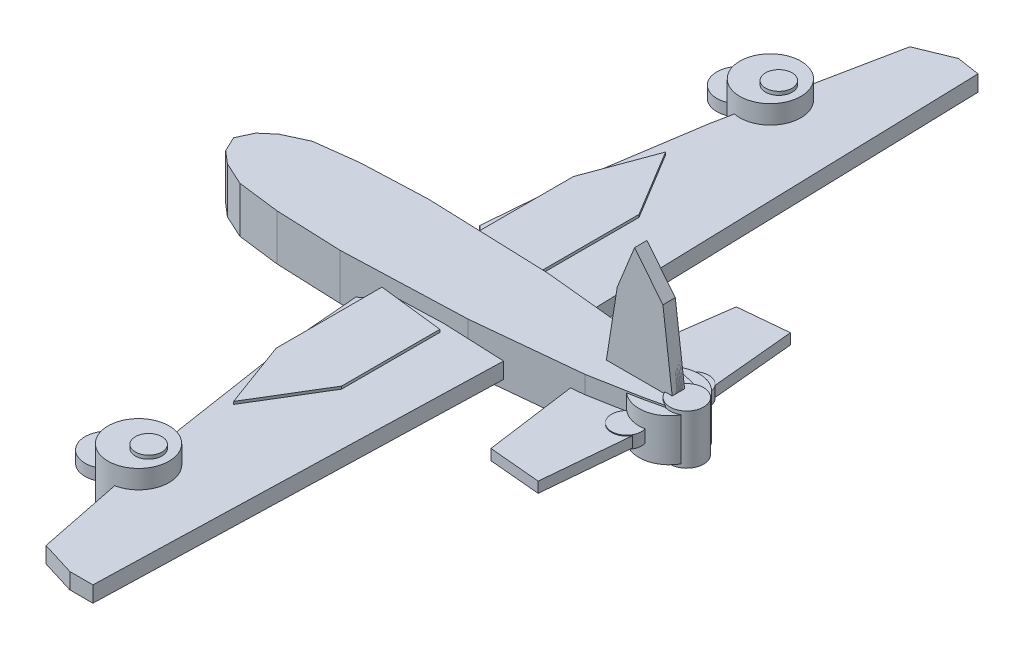
SolidWorks part; units mm, degrees
ref_plane "Front Plane" through (0, 0, 0) normal (0, 0, 1) x (1, 0, 0)
ref_plane "Top Plane" through (0, 0, 0) normal (0, 1, 0) x (1, 0, 0)
ref_plane "Right Plane" through (0, 0, 0) normal (1, 0, 0) x (0, 0, -1)
sketch "Sketch1" plane through (0, 0, 0) normal (0, 1, 0) x (1, 0, 0)
  line L0 (-1300, 0) -> (-1260, 85)
  line L1 (-1260, 85) -> (-1190, 145)
  line L2 (-1190, 145) -> (-1060, 205)
  line L3 (-1060, 205) -> (-820, 235)
  line L4 (-820, 235) -> (-450, 250)
  line L5 (-450, 250) -> (250, 225)
  line L6 (250, 225) -> (850, 165)
  line L7 (850, 165) -> (1120, 115)
  line L8 (1120, 115) -> (1250, 85)
  line L9 (1250, 85) -> (1300, 0)
  line L10 (1300, 0) -> (1250, -85)
  line L11 (1250, -85) -> (1120, -115)
  line L12 (1120, -115) -> (850, -165)
  line L13 (850, -165) -> (250, -225)
  line L14 (250, -225) -> (-450, -250)
  line L15 (-450, -250) -> (-820, -235)
  line L16 (-820, -235) -> (-1060, -205)
  line L17 (-1060, -205) -> (-1190, -145)
  line L18 (-1190, -145) -> (-1260, -85)
  line L19 (-1260, -85) -> (-1300, 0)
extrude "Boss-Extrude1" add sketch "Sketch1" along normal mid plane 260 separate body
sketch "Sketch2" plane through (0, 0, 0) normal (0, 1, 0) x (1, 0, 0)
  line L0 (400, 25) -> (400, 70.922)
  line L1 (400, 70.922) -> (362.961, 107.961)
  line L2 (362.961, 107.961) -> (330.4892, 140.4328)
  line L3 (330.4892, 140.4328) -> (280, 140.4328)
  line L4 (280, 140.4328) -> (-560, 140.4328)
  line L5 (-560, 140.4328) -> (-605.922, 140.4328)
  line L6 (-605.922, 140.4328) -> (-638.3938, 107.961)
  line L7 (-638.3938, 107.961) -> (-675.4328, 70.922)
  line L8 (-675.4328, 70.922) -> (-675.4328, 25)
  line L9 (-675.4328, 25) -> (-675.4328, -25)
  line L10 (-675.4328, -25) -> (-675.4328, -70.922)
  line L11 (-675.4328, -70.922) -> (-638.3938, -107.961)
  line L12 (-638.3938, -107.961) -> (-605.922, -140.4328)
  line L13 (-605.922, -140.4328) -> (-560, -140.4328)
  line L14 (-560, -140.4328) -> (280, -140.4328)
  line L15 (280, -140.4328) -> (330.4892, -140.4328)
  line L16 (330.4892, -140.4328) -> (362.961, -107.961)
  line L17 (362.961, -107.961) -> (400, -70.922)
  line L18 (400, -70.922) -> (400, -25)
  line L19 (400, -25) -> (400, 25)
extrude "Boss-Extrude2" add sketch "Sketch2" along normal mid plane 115 separate body
sketch "Sketch3" plane through (0, 0, 0) normal (0, 1, 0) x (1, 0, 0)
  circle A0 centre (-1080, 0) radius 125
extrude "Boss-Extrude3" add sketch "Sketch3" along normal mid plane 145 separate body
sketch "Sketch4" plane through (0, 0, 0) normal (0, 1, 0) x (1, 0, 0)
  line L0 (-110, 220) -> (470, 245)
  line L1 (470, 245) -> (405, 2500)
  line L2 (405, 2500) -> (275, 2520)
  line L3 (275, 2520) -> (80, 2440)
  line L4 (80, 2440) -> (-110, 1500)
  line L5 (-110, 1500) -> (-230, 720)
  line L6 (-230, 720) -> (-260, 350)
  line L7 (-260, 350) -> (-110, 220)
extrude "Boss-Extrude4" add sketch "Sketch4" along normal mid plane 90 separate body
sketch "Sketch5" plane through (0, 0, 0) normal (0, 1, 0) x (1, 0, 0)
  line L0 (-110, -220) -> (470, -245)
  line L1 (470, -245) -> (405, -2500)
  line L2 (405, -2500) -> (275, -2500)
  line L3 (275, -2500) -> (80, -2440)
  line L4 (80, -2440) -> (-110, -1500)
  line L5 (-110, -1500) -> (-230, -720)
  line L6 (-230, -720) -> (-260, -350)
  line L7 (-260, -350) -> (-110, -220)
extrude "Boss-Extrude5" add sketch "Sketch5" along normal mid plane 90 separate body
sketch "Sketch6" plane through (0, 0, 0) normal (0, 1, 0) x (1, 0, 0)
  line L0 (-220.293, 241.7962) -> (150, 285)
  line L1 (250, 225) -> (-450, 250) construction
  line L2 (150, 285) -> (150, 840)
  line L3 (150, 840) -> (-80, 1220)
  line L4 (-80, 1220) -> (-220.293, 840)
  line L5 (-220.293, 840) -> (-220.293, 241.7962)
extrude "Boss-Extrude6" add sketch "Sketch6" along normal mid plane 120 separate body
sketch "Sketch7" plane through (0, 0, 0) normal (0, 1, 0) x (1, 0, 0)
  line L0 (80, 1460) -> (407.2958, 2420.3544)
  line L1 (470, 245) -> (405, 2500) construction
  line L2 (407.2958, 2420.3544) -> (300.4863, 2456.7559)
  line L3 (300.4863, 2456.7559) -> (-22.4005, 1509.3383)
  line L4 (-22.4005, 1509.3383) -> (80, 1460)
extrude "Boss-Extrude7" add sketch "Sketch7" along normal mid plane 45 separate body
sketch "Sketch8" plane through (0, 0, 0) normal (0, 1, 0) x (1, 0, 0)
  line L0 (-220.293, -241.7962) -> (150, -285)
  line L1 (-450, -250) -> (250, -225) construction
  line L2 (150, -285) -> (150, -840)
  line L3 (150, -840) -> (-80, -1220)
  line L4 (-80, -1220) -> (-220.293, -840)
  line L5 (-220.293, -840) -> (-220.293, -241.7962)
extrude "Boss-Extrude8" add sketch "Sketch8" along normal mid plane 120 separate body
sketch "Sketch9" plane through (0, 0, 0) normal (0, 1, 0) x (1, 0, 0)
  line L0 (80, -1460) -> (407.2958, -2420.3544)
  line L1 (405, -2500) -> (470, -245) construction
  line L2 (407.2958, -2420.3544) -> (300.4863, -2456.7559)
  line L3 (300.4863, -2456.7559) -> (-22.4005, -1509.3383)
  line L4 (-22.4005, -1509.3383) -> (80, -1460)
extrude "Boss-Extrude9" add sketch "Sketch9" along normal mid plane 45 separate body
sketch "Sketch10" plane through (0, 0, 0) normal (0, 1, 0) x (1, 0, 0)
  line L0 (760, 60) -> (1185, 100)
  line L1 (1250, 85) -> (1120, 115) construction
  line L2 (1185, 100) -> (1126.7643, 718.7543)
  line L3 (1126.7643, 718.7543) -> (846.9488, 692.4187)
  line L4 (846.9488, 692.4187) -> (760, 60)
extrude "Boss-Extrude10" add sketch "Sketch10" along normal mid plane 60 separate body
sketch "Sketch11" plane through (0, 0, 0) normal (0, 1, 0) x (1, 0, 0)
  line L0 (760, -60) -> (1200, -60)
  line L1 (1200, -60) -> (1140, -720)
  line L2 (1140, -720) -> (846.9672, -693.3607)
  line L3 (846.9672, -693.3607) -> (760, -60)
extrude "Boss-Extrude11" add sketch "Sketch11" along normal mid plane 60 separate body
sketch "Sketch12" plane through (0, 0, 0) normal (0, 0, 1) x (1, 0, 0)
  line L0 (820, 0) -> (1230, 0)
  line L1 (1230, 0) -> (1160, 560)
  line L2 (1160, 560) -> (1000, 760)
  line L3 (1000, 760) -> (901.9512, 517.561)
  line L4 (901.9512, 517.561) -> (820, 0)
extrude "Boss-Extrude12" add sketch "Sketch12" along normal mid plane 70 separate body
sketch "Sketch13" plane through (0, 0, 0) normal (0, 0, 1) x (1, 0, 0)
  line L0 (1030, 0) -> (1230, 0)
  line L1 (1230, 0) -> (1181.2308, 390.1538)
  line L2 (1230, 0) -> (1160, 560) construction
  line L3 (1181.2308, 390.1538) -> (1091.9231, 459.6154)
  line L4 (1091.9231, 459.6154) -> (1043.4231, 305.1154)
  line L5 (1043.4231, 305.1154) -> (1030, 0)
extrude "Boss-Extrude13" add sketch "Sketch13" along normal mid plane 55 separate body
sketch "Sketch14" plane through (0, 0, 0) normal (0, 1, 0) x (1, 0, 0)
  line L0 (80, 2440) -> (-110, 1500) construction
  circle A0 centre (-52.4856, 1784.545) radius 172.4856
extrude "Boss-Extrude14" add sketch "Sketch14" along normal mid plane 300 separate body
sketch "Sketch15" plane through (0, 0, 0) normal (0, 1, 0) x (1, 0, 0)
  line L0 (-110, -1500) -> (80, -2440) construction
  circle A0 centre (-52.4856, -1784.545) radius 172.4856
extrude "Boss-Extrude15" add sketch "Sketch15" along normal mid plane 300 separate body
sketch "Sketch16" plane through (0, 0, 0) normal (0, 1, 0) x (1, 0, 0)
  line L0 (1160, -35) -> (1160, 35) construction
  circle A0 centre (1160, 0) radius 170
extrude "Boss-Extrude16" add sketch "Sketch16" along normal mid plane 240 separate body
sketch "Sketch17" plane through (0, 0, 0) normal (0, 1, 0) x (1, 0, 0)
  circle A0 centre (0, 1780) radius 75
extrude "Boss-Extrude17" add sketch "Sketch17" along normal mid plane 340 separate body
sketch "Sketch18" plane through (0, 0, 0) normal (0, 1, 0) x (1, 0, 0)
  circle A0 centre (0, -1780) radius 75
extrude "Boss-Extrude18" add sketch "Sketch18" along normal mid plane 340 separate body
sketch "Sketch19" plane through (0, 0, 0) normal (0, 1, 0) x (1, 0, 0)
  circle A0 centre (1260, 0) radius 95
extrude "Boss-Extrude19" add sketch "Sketch19" along normal mid plane 280 separate body
sketch "Sketch20" plane through (0, 0, 0) normal (0, 1, 0) x (1, 0, 0)
  circle A0 centre (-224.9712, 1784.545) radius 129.9712
  circle A1 centre (-52.4856, 1784.545) radius 172.4856 construction
extrude "Boss-Extrude20" add sketch "Sketch20" along normal mid plane 65 separate body
sketch "Sketch21" plane through (0, 0, 0) normal (0, 1, 0) x (1, 0, 0)
  circle A0 centre (1110, 190) radius 85
extrude "Boss-Extrude21" add sketch "Sketch21" along normal mid plane 70 separate body
sketch "Sketch22" plane through (0, 0, 0) normal (0, 1, 0) x (1, 0, 0)
  circle A0 centre (-224.9712, -1784.545) radius 129.9712
  circle A1 centre (-52.4856, -1784.545) radius 172.4856 construction
extrude "Boss-Extrude22" add sketch "Sketch22" along normal mid plane 65 separate body
sketch "Sketch23" plane through (0, 0, 0) normal (0, 1, 0) x (1, 0, 0)
  circle A0 centre (1110, -190) radius 85
extrude "Boss-Extrude23" add sketch "Sketch23" along normal mid plane 70 separate body
sketch "Sketch24" plane through (0, 0, 0) normal (0, 1, 0) x (1, 0, 0)
  circle A0 centre (-1080, 0) radius 125
extrude "Boss-Extrude24" add sketch "Sketch24" along normal mid plane 90 separate body
sketch "Sketch25" plane through (0, 0, 0) normal (0, 0, 1) x (1, 0, 0)
  circle A0 centre (-1135, -45) radius 75
extrude "Boss-Extrude25" add sketch "Sketch25" along normal mid plane 110 separate body
